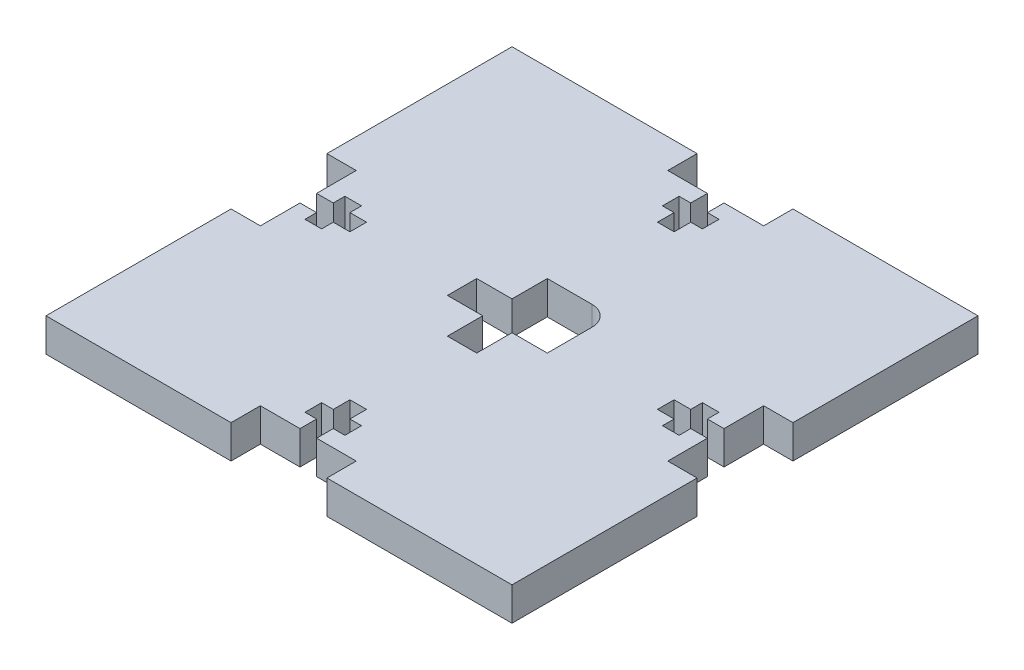
SolidWorks part; units mm, degrees
ref_plane "Front Plane" through (0, 0, 0) normal (0, 0, 1) x (1, 0, 0)
ref_plane "Top Plane" through (0, 0, 0) normal (0, 1, 0) x (1, 0, 0)
ref_plane "Right Plane" through (0, 0, 0) normal (1, 0, 0) x (0, 0, -1)
sketch "Sketch1" plane through (0, 0, 0) normal (0, 1, 0) x (1, 0, 0)
  line L1 (0, 0) -> (88.9, 0)
  line L2 (0, 0) -> (0, 88.9)
  line L3 (0, 88.9) -> (88.9, 88.9)
  line L4 (88.9, 0) -> (88.9, 88.9)
  dimension "D1" = 88.9
  dimension "D2" = 88.9
extrude "Boss-Extrude1" add sketch "Sketch1" along normal blind 6.35
sketch "Sketch5" plane through (0, 6.35, 0) normal (0, 1, 0) x (1, 0, 0)
  line L0 (44.45, 88.9) -> (44.45, 0) construction
  line L1 (41.656, 47.244) -> (41.656, 53.975)
  line L2 (34.925, 41.656) -> (41.656, 41.656)
  line L3 (34.925, 41.656) -> (34.925, 47.244)
  line L4 (34.925, 47.244) -> (41.656, 47.244)
  line L5 (53.975, 41.656) -> (53.975, 47.244)
  line L6 (34.925, 41.656) -> (53.975, 47.244) construction
  line L7 (0, 44.45) -> (88.9, 44.45) construction
  line L8 (34.925, 47.244) -> (53.975, 41.656) construction
  line L9 (47.244, 34.925) -> (41.656, 34.925)
  line L10 (47.244, 34.925) -> (47.244, 41.656)
  line L11 (47.244, 53.975) -> (41.656, 53.975)
  line L12 (41.656, 34.925) -> (41.656, 41.656)
  line L13 (47.244, 34.925) -> (41.656, 53.975) construction
  line L14 (47.244, 53.975) -> (41.656, 34.925) construction
  line L15 (47.244, 41.656) -> (53.975, 41.656)
  line L16 (88.9, 88.9) -> (0, 88.9) construction
  line L17 (88.9, 0) -> (88.9, 88.9) construction
  line L18 (0, -3.4925) -> (0, 3.4925) construction
  line L19 (-3.4925, 0) -> (3.4925, 0) construction
  line L20 (47.244, 47.244) -> (47.244, 53.975)
  line L21 (47.244, 47.244) -> (53.975, 47.244)
  point P0 (44.45, 44.45)
  point P16 (42.8625, 44.45)
  point P17 (44.45, 44.45)
  point P23 (41.656, 47.244)
  point P24 (47.244, 47.244)
  point P25 (47.244, 41.656)
  point P26 (41.656, 41.656)
  dimension "D1" = 19.05
  dimension "D2" = 5.588
  dimension "D3" = 19.05
  dimension "D4" = 5.588
extrude "Cut-Extrude3" cut sketch "Sketch5" against normal through all
sketch "Sketch4" plane through (0, 6.35, 0) normal (0, 1, 0) x (1, 0, 0)
  line L0 (88.9, 88.9) -> (0, 88.9) construction
  line L1 (35.306, 88.9) -> (53.594, 88.9)
  line L2 (35.306, 88.9) -> (35.306, 83.312)
  line L3 (35.306, 83.312) -> (53.594, 83.312)
  line L4 (53.594, 88.9) -> (53.594, 83.312)
  line L5 (88.9, 0) -> (88.9, 88.9) construction
  line L6 (-3.4925, 0) -> (3.4925, 0) construction
  line L7 (88.9, 53.594) -> (83.312, 53.594)
  line L8 (88.9, 53.594) -> (88.9, 35.306)
  line L9 (83.312, 53.594) -> (83.312, 35.306)
  line L10 (88.9, 35.306) -> (83.312, 35.306)
  line L11 (53.594, 0) -> (53.594, 5.588)
  line L12 (53.594, 0) -> (35.306, 0)
  line L13 (53.594, 5.588) -> (35.306, 5.588)
  line L14 (35.306, 0) -> (35.306, 5.588)
  line L15 (0, 35.306) -> (5.588, 35.306)
  line L16 (0, 35.306) -> (0, 53.594)
  line L17 (5.588, 35.306) -> (5.588, 53.594)
  line L18 (0, 53.594) -> (5.588, 53.594)
  line L20 (88.9, 44.45) -> (0, 44.45) construction
  line L21 (0, -3.4925) -> (0, 3.4925) construction
  line L22 (44.45, 0) -> (44.45, 88.9) construction
  point P8 (50.8, 38.1)
  point P11 (44.45, 88.9)
  point P19 (88.9, 44.45)
  point P24 (44.45, 0)
  point P29 (0, 44.45)
  point P30 (44.45, 44.45)
  point P34 (44.45, 44.45)
  dimension "D1" = 5.588
  dimension "D2" = 18.288
  dimension "D4" = 38.1
  dimension "D5" = 38.1
  dimension "D6" = 4
extrude "Cut-Extrude2" cut sketch "Sketch4" against normal through all
sketch "Sketch7" plane through (0, 6.35, 0) normal (0, 1, 0) x (1, 0, 0)
  line L0 (41.656, 53.975) -> (53.975, 53.975) construction
  line L1 (53.975, 41.656) -> (53.975, 53.975) construction
  line L3 (53.975, 53.975) -> (47.244, 53.975)
  line L4 (53.975, 53.975) -> (53.975, 47.244)
  line L5 (53.975, 47.244) -> (47.244, 47.244)
  line L6 (47.244, 53.975) -> (47.244, 47.244)
extrude "Cut-Extrude4" cut sketch "Sketch7" against normal through all
fillet "Fillet1" radius 3.81 1 edges at (53.975, 3.175, -53.975)
sketch "Sketch8" plane through (0, 6.35, 0) normal (0, 1, 0) x (1, 0, 0)
  line L0 (5.588, 35.306) -> (5.588, 53.594) construction
  line L1 (5.588, 42.8625) -> (8.763, 42.8625)
  line L2 (5.588, 42.8625) -> (5.588, 46.0375)
  line L3 (5.588, 46.0375) -> (8.763, 46.0375)
  line L4 (15.113, 42.8625) -> (15.113, 46.0375)
  line L5 (5.588, 42.8625) -> (15.113, 46.0375) construction
  line L6 (5.588, 46.0375) -> (15.113, 42.8625) construction
  line L7 (8.763, 40.64) -> (11.938, 40.64)
  line L8 (8.763, 40.64) -> (8.763, 42.8625)
  line L9 (8.763, 48.26) -> (11.938, 48.26)
  line L10 (11.938, 40.64) -> (11.938, 42.8625)
  line L11 (8.763, 40.64) -> (11.938, 48.26) construction
  line L12 (8.763, 48.26) -> (11.938, 40.64) construction
  line L13 (5.588, 35.306) -> (5.588, 53.594) construction
  line L14 (35.306, 83.312) -> (53.594, 83.312) construction
  line L15 (35.306, 83.312) -> (53.594, 83.312) construction
  line L16 (44.45, 83.312) -> (44.45, 44.45) construction
  line L17 (44.45, 44.45) -> (5.588, 44.45) construction
  line L18 (8.763, 46.0375) -> (8.763, 48.26)
  line L19 (11.938, 46.0375) -> (15.113, 46.0375)
  line L20 (11.938, 46.0375) -> (11.938, 48.26)
  line L21 (11.938, 42.8625) -> (15.113, 42.8625)
  line L22 (42.8625, 83.312) -> (42.8625, 80.137)
  line L23 (42.8625, 83.312) -> (46.0375, 83.312)
  line L24 (46.0375, 83.312) -> (46.0375, 80.137)
  line L25 (42.8625, 73.787) -> (46.0375, 73.787)
  line L26 (40.64, 80.137) -> (40.64, 76.962)
  line L27 (40.64, 80.137) -> (42.8625, 80.137)
  line L28 (48.26, 80.137) -> (48.26, 76.962)
  line L29 (40.64, 76.962) -> (42.8625, 76.962)
  line L30 (46.0375, 80.137) -> (48.26, 80.137)
  line L31 (46.0375, 76.962) -> (46.0375, 73.787)
  line L32 (46.0375, 76.962) -> (48.26, 76.962)
  line L33 (42.8625, 76.962) -> (42.8625, 73.787)
  line L34 (42.8625, 83.312) -> (46.0375, 73.787) construction
  line L35 (46.0375, 83.312) -> (42.8625, 73.787) construction
  line L36 (40.64, 80.137) -> (48.26, 76.962) construction
  line L37 (48.26, 80.137) -> (40.64, 76.962) construction
  line L38 (83.312, 46.0375) -> (80.137, 46.0375)
  line L39 (83.312, 46.0375) -> (83.312, 42.8625)
  line L40 (83.312, 42.8625) -> (80.137, 42.8625)
  line L41 (73.787, 46.0375) -> (73.787, 42.8625)
  line L42 (80.137, 48.26) -> (76.962, 48.26)
  line L43 (80.137, 48.26) -> (80.137, 46.0375)
  line L44 (80.137, 40.64) -> (76.962, 40.64)
  line L45 (76.962, 48.26) -> (76.962, 46.0375)
  line L46 (80.137, 42.8625) -> (80.137, 40.64)
  line L47 (76.962, 42.8625) -> (73.787, 42.8625)
  line L48 (76.962, 42.8625) -> (76.962, 40.64)
  line L49 (76.962, 46.0375) -> (73.787, 46.0375)
  line L50 (83.312, 46.0375) -> (73.787, 42.8625) construction
  line L51 (83.312, 42.8625) -> (73.787, 46.0375) construction
  line L52 (80.137, 48.26) -> (76.962, 40.64) construction
  line L53 (80.137, 40.64) -> (76.962, 48.26) construction
  line L54 (46.0375, 5.588) -> (46.0375, 8.763)
  line L55 (46.0375, 5.588) -> (42.8625, 5.588)
  line L56 (42.8625, 5.588) -> (42.8625, 8.763)
  line L57 (46.0375, 15.113) -> (42.8625, 15.113)
  line L58 (48.26, 8.763) -> (48.26, 11.938)
  line L59 (48.26, 8.763) -> (46.0375, 8.763)
  line L60 (40.64, 8.763) -> (40.64, 11.938)
  line L61 (48.26, 11.938) -> (46.0375, 11.938)
  line L62 (42.8625, 8.763) -> (40.64, 8.763)
  line L63 (42.8625, 11.938) -> (42.8625, 15.113)
  line L64 (42.8625, 11.938) -> (40.64, 11.938)
  line L65 (46.0375, 11.938) -> (46.0375, 15.113)
  line L66 (46.0375, 5.588) -> (42.8625, 15.113) construction
  line L67 (42.8625, 5.588) -> (46.0375, 15.113) construction
  line L68 (48.26, 8.763) -> (40.64, 11.938) construction
  line L69 (40.64, 8.763) -> (48.26, 11.938) construction
  point P0 (10.3505, 44.45)
  point P5 (10.3505, 44.45)
  point P24 (44.45, 78.5495)
  point P29 (44.45, 78.5495)
  point P38 (78.5495, 44.45)
  point P43 (78.5495, 44.45)
  point P52 (44.45, 10.3505)
  point P57 (44.45, 10.3505)
  point P66 (44.45, 44.45)
  dimension "D1" = 3.175
  dimension "D2" = 7.62
  dimension "D3" = 9.525
  dimension "D4" = 3.175
  dimension "D5" = 4
extrude "Cut-Extrude5" cut sketch "Sketch8" against normal through all
